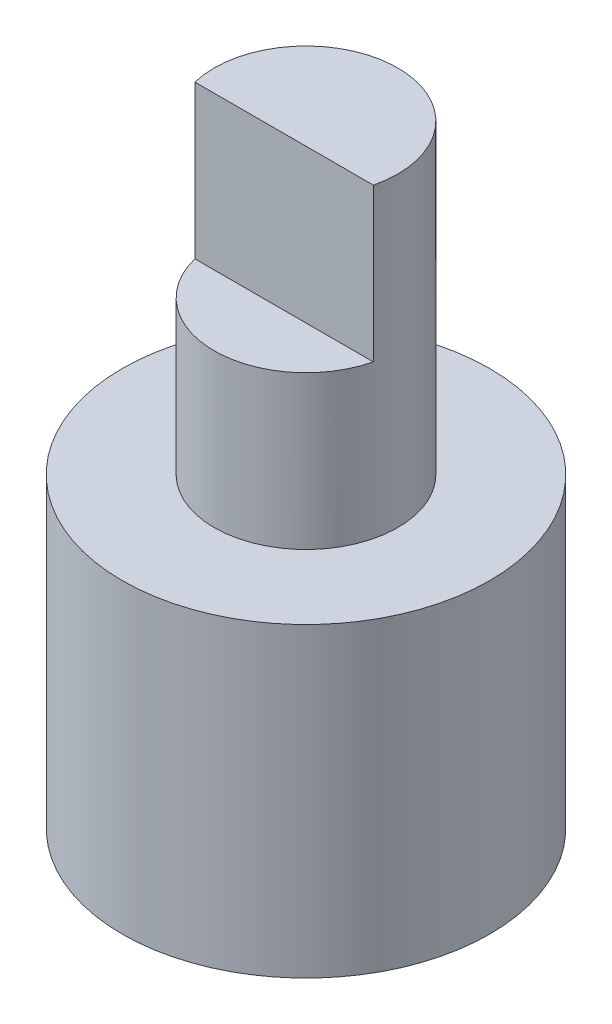
SolidWorks part; units mm, degrees
ref_plane "Front Plane" through (0, 0, 0) normal (0, 0, 1) x (1, 0, 0)
ref_plane "Top Plane" through (0, 0, 0) normal (0, 1, 0) x (1, 0, 0)
ref_plane "Right Plane" through (0, 0, 0) normal (1, 0, 0) x (0, 0, -1)
sketch "Sketch2" plane through (0, 0, 0) normal (0, 1, 0) x (1, 0, 0)
  circle A0 centre (0, 0) radius 3
  dimension "D1" = 6
extrude "Boss-Extrude1" add sketch "Sketch2" along normal blind 5
sketch "Sketch3" plane through (0, 5, 0) normal (0, 1, 0) x (1, 0, 0)
  circle A0 centre (0, 0) radius 1.5
extrude "Boss-Extrude2" add sketch "Sketch3" along normal blind 5
sketch "Sketch4" plane through (0, 10, 0) normal (0, 1, 0) x (1, 0, 0)
  line L0 (-1.4569, -0.357) -> (1.4569, -0.357)
  circle A0 centre (0, 0) radius 1.5 construction
  arc A1 (-1.4569, -0.357) -> (1.4569, -0.357) centre (0, 0) ccw
  dimension "D1" = 2.9138
extrude "Cut-Extrude1" cut sketch "Sketch4" against normal blind 2.5
